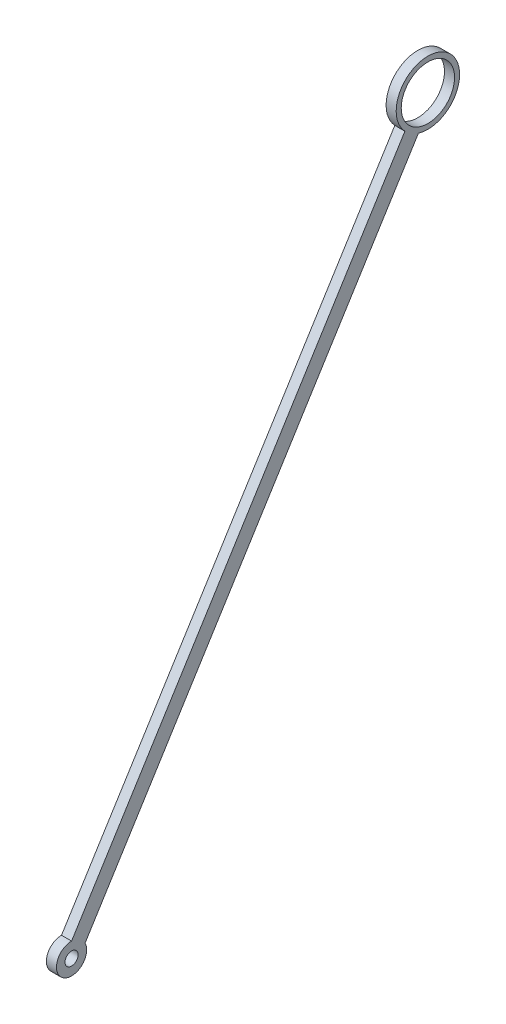
SolidWorks part; units mm, degrees
ref_plane "Front Plane" through (0, 0, 0) normal (0, 0, 1) x (1, 0, 0)
ref_plane "Top Plane" through (0, 0, 0) normal (0, 1, 0) x (1, 0, 0)
ref_plane "Right Plane" through (0, 0, 0) normal (1, 0, 0) x (0, 0, -1)
sketch "Sketch1" plane through (16.0048, 0, 0) normal (-1, 0, 0) x (0, 0, 1)
  line L0 (43.4886, 61.4064) -> (10.3822, 114.5141)
  line L1 (8.0962, 116.6813) -> (43.4886, 59.9064) construction
  line L2 (42.1418, 60.5668) -> (9.0354, 113.6746)
  circle A0 centre (8.0962, 116.6813) radius 2.65
  arc A1 (10.3822, 114.5141) -> (9.0354, 113.6746) centre (8.0962, 116.6813) ccw
  circle A2 centre (8.0962, 116.6813) radius 2.65 construction
  circle A3 centre (43.4886, 59.9064) radius 0.65 construction
  circle A4 centre (43.4886, 59.9064) radius 1.5
  arc A5 (42.1418, 60.5668) -> (43.4886, 61.4064) centre (43.4886, 59.9064) ccw
  circle A6 centre (43.4886, 59.9064) radius 0.65
  dimension "D1" = 0.5
  dimension "D2" = 0
extrude "Boss-Extrude1" add sketch "Sketch1" along normal blind 1
